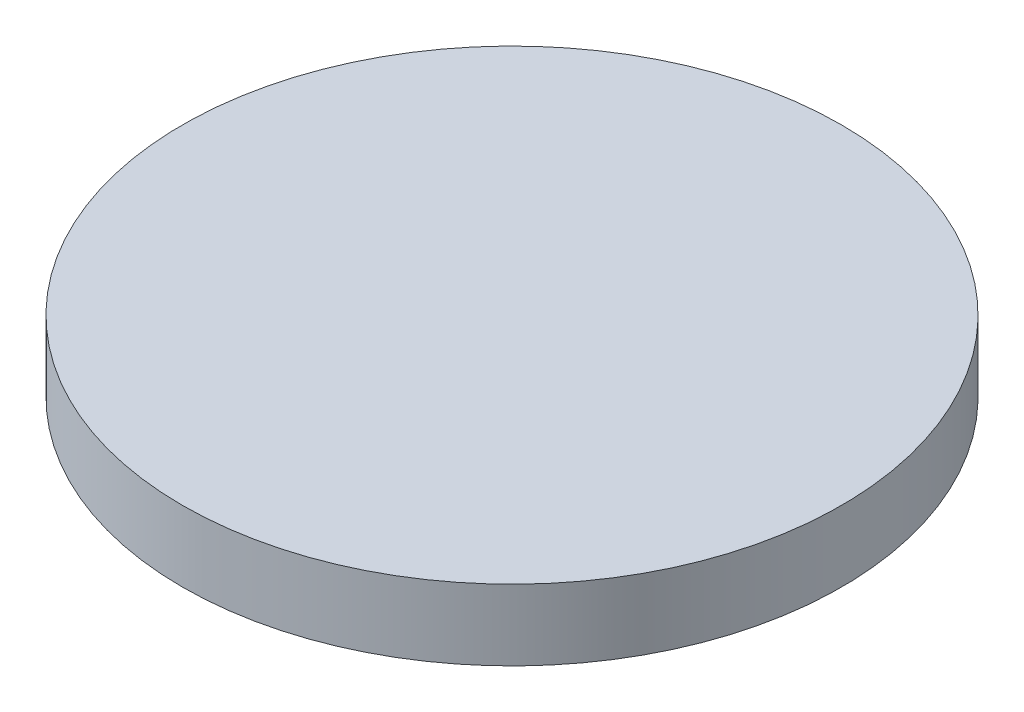
SolidWorks part; units mm, degrees
ref_plane "Front Plane" through (0, 0, 0) normal (0, 0, 1) x (1, 0, 0)
ref_plane "Top Plane" through (0, 0, 0) normal (0, 1, 0) x (1, 0, 0)
ref_plane "Right Plane" through (0, 0, 0) normal (1, 0, 0) x (0, 0, -1)
sketch "Sketch1" plane through (0, 0, 0) normal (0, 1, 0) x (1, 0, 0)
  circle A0 centre (0, 0) radius 39.8971
  circle A1 centre (0, 0) radius 41.8971
  dimension "D1" = 79.7942
  dimension "D2" = 2
extrude "Boss-Extrude1" add sketch "Sketch1" along normal blind 7
sketch "Sketch2" plane through (0, 7, 0) normal (0, 1, 0) x (1, 0, 0)
  circle A0 centre (0, 0) radius 41.8971
extrude "Boss-Extrude2" add sketch "Sketch2" along normal blind 2
equation "\"[R][Body] Capacity\"= 750'mL"
equation "\"[R][Body] Height\"= 8 * 2.54'cm"
equation "\"[R][Body] Radius\"= \"[R][Body] Capacity\" / \"[R][Body] Height\" / ( PI ^ 2 )'cm"
equation "\"[R][Body] Thickness\"= 0.25'cm"
equation "\"[TOL] Sliding\"= 0.5mm"
equation "\"[R][Slider] Height\"= 1"
equation "\"[R][Slider] Shell Thickness\" = 2mm"
equation "\"[R][Bottom] Height\"= \"[R][Bottom] Thread Height\" + 0.5cm"
equation "\"[R][Bottom] Reservoir Height\"= \"[R][Slider] Height\" + 0.5cm"
equation "\"[R][Bottom] Radius\" = \"[R][Body] Radius\" + \"[R][Body] Thickness\" + 0.5cm"
equation "\"[R][Bottom] Thread Height\"= 2cm"
equation "\"[R][Bottom] Thread Count\"= 4"
equation "\"[R][Bottom] Thread Length\"= 2 * PI * \"[R][Bottom] Radius\" / \"[R][Bottom] Thread Count\""
equation "\"[R][Bottom] Thread Thickness\" = 0.65cm"
equation "\"[R][Bottom] Thread Extrusion\"= 0.5cm"
equation "\"[R][Bottom] Inner Radius\"= \"[R][Body] Radius\" - 0.5cm"
equation "\"[R][Lid] Reservoir Height\"= 0.5cm"
equation "\"[R][Lid] Shell Thickness\"= 2mm"
equation "\"D1@Sketch1\"=(\"[R][Body] Radius\"+\"[R][Body] Thickness\")*2"
equation "\"D2@Sketch1\"=\"[R][Lid] Shell Thickness\""
equation "\"D1@Boss-Extrude1\"=\"[R][Lid] Reservoir Height\"+\"[R][Lid] Shell Thickness\""
equation "\"D1@Boss-Extrude2\"=\"[R][Lid] Shell Thickness\""
